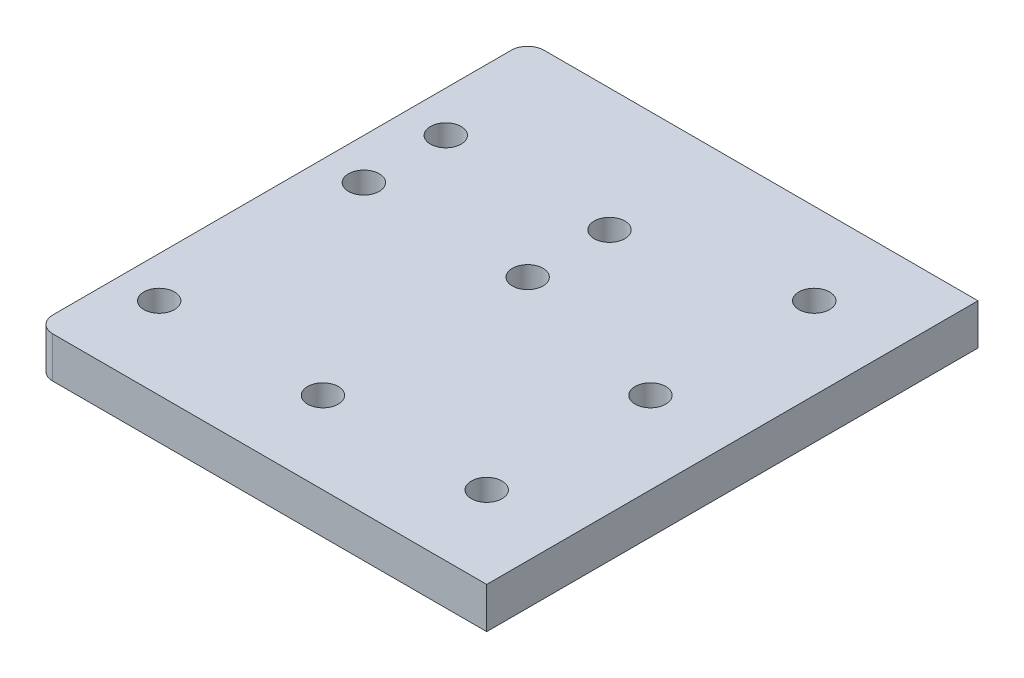
SolidWorks part; units mm, degrees
material "6063-T1"
ref_plane "Front Plane" through (0, 0, 0) normal (0, 0, 1) x (1, 0, 0)
ref_plane "Top Plane" through (0, 0, 0) normal (0, 1, 0) x (1, 0, 0)
ref_plane "Right Plane" through (0, 0, 0) normal (1, 0, 0) x (0, 0, -1)
sketch "Sketch1" plane through (0, 0, 0) normal (0, 1, 0) x (1, 0, 0)
  line L1 (-34.925, 38.1) -> (34.925, 38.1)
  line L2 (-34.925, 38.1) -> (-34.925, -38.1)
  line L3 (-34.925, -38.1) -> (34.925, -38.1)
  line L4 (34.925, 38.1) -> (34.925, -38.1)
  line L5 (-34.925, 38.1) -> (34.925, -38.1) construction
  line L6 (-34.925, -38.1) -> (34.925, 38.1) construction
  circle A0 centre (22.225, 0) radius 2.3812
  circle A1 centre (22.225, -25.4) radius 2.3812
  circle A2 centre (22.225, 25.4) radius 2.3812
  circle A3 centre (-28.575, -25.4) radius 2.3813
  circle A4 centre (-28.575, 19.05) radius 2.3813
  circle A5 centre (-28.575, 6.35) radius 2.3813
  circle A6 centre (-3.175, -25.4) radius 2.3813
  circle A7 centre (-3.175, 19.05) radius 2.3813
  circle A8 centre (-3.175, 6.35) radius 2.3813
  point P0 (0, 0)
  dimension "D5" = 4.7625
  dimension "D6" = 4.7625
  dimension "D7" = 4.7625
  dimension "D14" = 4.7625
  dimension "D16" = 4.7625
  dimension "D19" = 4.7625
  dimension "D1" = 69.85
  dimension "D2" = 76.2
  dimension "D3" = 25.4
  dimension "D4" = 12.7
  dimension "D8" = 12.7
  dimension "D9" = 12.7
  dimension "D10" = 12.7
  dimension "D11" = 12.7
  dimension "D12" = 6.35
  dimension "D13" = 12.7
  dimension "D15" = 44.45
  dimension "D17" = 31.75
  dimension "D18" = 6.35
  dimension "D20" = 6.35
  dimension "D21" = 2
extrude "Boss-Extrude1" add sketch "Sketch1" along normal blind 6.35
fillet "Fillet1" radius 2.54 2 edges at (-34.925, 3.175, -38.1) (-34.925, 3.175, 38.1)
